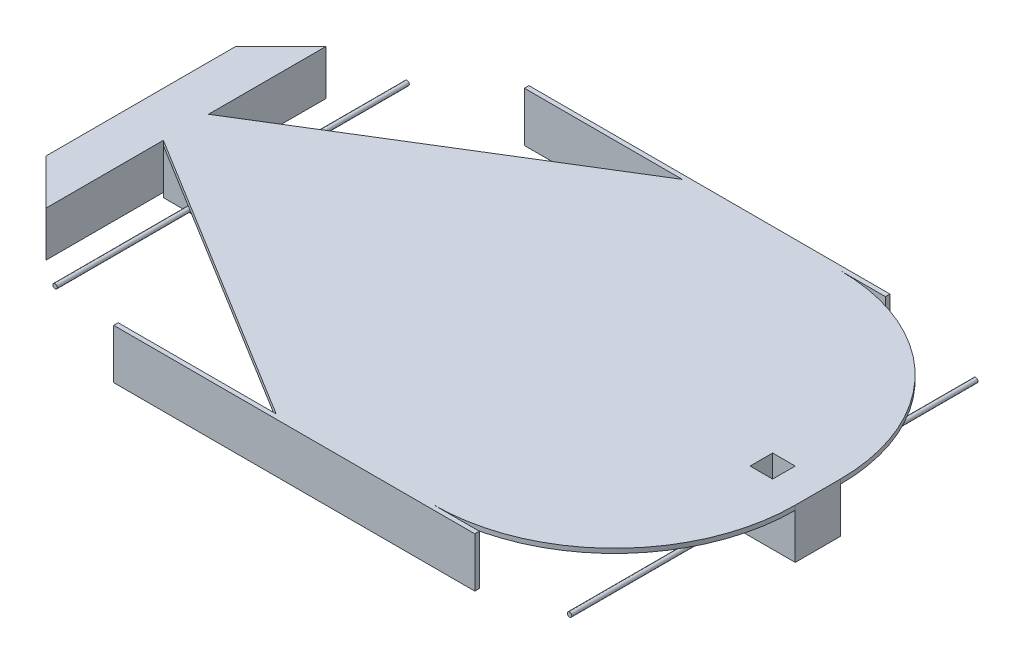
SolidWorks part; units mm, degrees
ref_plane "Front Plane" through (0, 0, 0) normal (0, 0, 1) x (1, 0, 0)
ref_plane "Top Plane" through (0, 0, 0) normal (0, 1, 0) x (1, 0, 0)
ref_plane "Right Plane" through (0, 0, 0) normal (1, 0, 0) x (0, 0, -1)
sketch "Sketch1" plane through (0, 0, 0) normal (0, 0, 1) x (1, 0, 0)
  line L1 (889, -63.5) -> (-889, -63.5)
  line L2 (889, -63.5) -> (889, 63.5)
  line L3 (889, 63.5) -> (-889, 63.5)
  line L4 (-889, -63.5) -> (-889, 63.5)
  line L5 (889, -63.5) -> (-889, 63.5) construction
  line L6 (889, 63.5) -> (-889, -63.5) construction
  point P0 (0, 0)
  point P6 (-508, -63.5)
  dimension "D1" = 1778
  dimension "D2" = 127
extrude "Boss-Extrude1" add sketch "Sketch1" along normal blind 127
sketch "Sketch2" plane through (0, 0, 127) normal (0, 0, 1) x (1, 0, 0)
  line L0 (-889, -63.5) -> (889, -63.5) construction
  line L1 (-63.5, 63.5) -> (63.5, 63.5)
  line L2 (-63.5, 63.5) -> (-63.5, -63.5)
  line L3 (-63.5, -63.5) -> (63.5, -63.5)
  line L4 (63.5, 63.5) -> (63.5, -63.5)
  line L5 (-63.5, 63.5) -> (63.5, -63.5) construction
  line L6 (-63.5, -63.5) -> (63.5, 63.5) construction
  point P0 (0, 0)
  dimension "D1" = 127
extrude "Boss-Extrude2" add sketch "Sketch2" along normal blind 508
sketch "Sketch3" plane through (0, 0, 0) normal (0, 0, -1) x (-1, 0, 0)
  line L1 (-63.5, 63.5) -> (63.5, 63.5)
  line L2 (-63.5, 63.5) -> (-63.5, -63.5)
  line L3 (-63.5, -63.5) -> (63.5, -63.5)
  line L4 (63.5, 63.5) -> (63.5, -63.5)
  line L5 (-63.5, 63.5) -> (63.5, -63.5) construction
  line L6 (-63.5, -63.5) -> (63.5, 63.5) construction
  point P0 (0, 0)
extrude "Boss-Extrude3" add sketch "Sketch3" along normal blind 508
sketch "Sketch4" plane through (0, 0, 127) normal (0, 0, 1) x (1, 0, 0)
  line L0 (-889, 0) -> (-762, 0) construction
  line L1 (-889, 63.5) -> (-889, -63.5) construction
  circle A0 centre (-762, 0) radius 6.35
  dimension "D2" = 12.7
  dimension "D1" = 127
extrude "Boss-Extrude4" add sketch "Sketch4" along normal blind 431.8 and the other way blind 558.8
sketch "Sketch6" plane through (0, 0, 127) normal (0, 0, 1) x (1, 0, 0)
  line L0 (889, 0) -> (762, 0) construction
  line L1 (889, -63.5) -> (889, 63.5) construction
  circle A0 centre (762, 0) radius 6.35
  dimension "D2" = 12.7
  dimension "D1" = 127
extrude "Boss-Extrude5" add sketch "Sketch6" along normal blind 508 and the other way blind 635
sketch "Sketch9" plane through (0, 63.5, 0) normal (0, 1, 0) x (1, 0, 0)
  line L0 (-63.5, -63.5) -> (889, -63.5) construction
  line L2 (889, -127) -> (889, 0) construction
  line L3 (0, 508) -> (0, -635) construction
  line L4 (-63.5, 508) -> (63.5, 508) construction
  line L5 (63.5, -635) -> (-63.5, -635) construction
  line L6 (-63.5, 508) -> (-63.5, -635)
  line L7 (-63.5, -635) -> (381, -635)
  line L9 (-63.5, 508) -> (381, 508)
  line L10 (889, -127) -> (889, 0)
  line L11 (-63.5, -635) -> (889, 508) construction
  line L12 (-63.5, 508) -> (889, -635) construction
  arc A0 (381, 508) -> (889, 0) centre (381, 0) cw
  arc A1 (889, -127) -> (381, -635) centre (381, -127) cw
  point P12 (412.75, -63.5)
  dimension "D2" = 508
  dimension "D1" = 952.5
extrude "Boss-Extrude7" add sketch "Sketch9" along normal blind 12.7
sketch "Sketch10" plane through (0, 63.5, 0) normal (0, 1, 0) x (1, 0, 0)
  line L0 (-63.5, -635) -> (-889, -127)
  line L1 (-889, -127) -> (-889, 0)
  line L2 (-889, 0) -> (-63.5, 508)
  line L7 (381, 508) -> (-63.5, 508)
  line L8 (-63.5, 508) -> (-63.5, -635)
  line L9 (-63.5, -635) -> (381, -635)
  line L10 (889, -127) -> (889, 0)
  line L11 (381, 508) -> (-63.5, 508)
  line L13 (-63.5, -635) -> (381, -635)
  line L14 (889, -127) -> (889, 0)
  arc A2 (889, 0) -> (381, 508) centre (381, 0) ccw
  arc A3 (381, -635) -> (889, -127) centre (381, -127) ccw
  arc A4 (889, 0) -> (381, 508) centre (381, 0) ccw
  arc A5 (381, -635) -> (889, -127) centre (381, -127) ccw
  dimension "D1" = 0
extrude "Boss-Extrude8" add sketch "Sketch10" along normal blind 12.7
sketch "Sketch11" plane through (0, 0, -508) normal (0, 0, -1) x (-1, 0, 0)
  line L0 (-63.5, 76.2) -> (-63.5, -63.5) construction
  line L1 (-381, 76.2) -> (63.5, 76.2) construction
  line L2 (-63.5, -63.5) -> (63.5, -63.5) construction
  line L3 (63.5, -63.5) -> (63.5, 76.2) construction
  line L4 (63.5, 76.2) -> (-63.5, 76.2) construction
  line L5 (0, 76.2) -> (0, -63.5) construction
  line L6 (-63.5, 6.35) -> (63.5, 6.35) construction
  line L8 (-508, -63.5) -> (508, -63.5)
  line L9 (-508, -63.5) -> (-508, 76.2)
  line L10 (-508, 76.2) -> (508, 76.2)
  line L11 (508, -63.5) -> (508, 76.2)
  line L12 (-508, -63.5) -> (508, 76.2) construction
  line L13 (-508, 76.2) -> (508, -63.5) construction
  point P13 (0, 6.35)
  dimension "D1" = 139.7
  dimension "D2" = 1016
extrude "Boss-Extrude9" add sketch "Sketch11" along normal blind 12.7
sketch "Sketch12" plane through (0, 0, 635) normal (0, 0, 1) x (1, 0, 0)
  line L0 (-63.5, -63.5) -> (-63.5, 76.2) construction
  line L1 (-63.5, 76.2) -> (63.5, 76.2) construction
  line L2 (-63.5, 76.2) -> (381, 76.2) construction
  line L3 (63.5, 76.2) -> (63.5, -63.5) construction
  line L4 (63.5, -63.5) -> (-63.5, -63.5) construction
  line L5 (0, 76.2) -> (0, -63.5) construction
  line L6 (-63.5, 6.35) -> (63.5, 6.35) construction
  line L7 (63.5, -63.5) -> (889, -63.5) construction
  line L8 (-508, 76.2) -> (508, 76.2)
  line L9 (-508, 76.2) -> (-508, -63.5)
  line L10 (-508, -63.5) -> (508, -63.5)
  line L11 (508, 76.2) -> (508, -63.5)
  line L12 (-508, 76.2) -> (508, -63.5) construction
  line L13 (-508, -63.5) -> (508, 76.2) construction
  point P13 (0, 6.35)
  dimension "D1" = 1016
extrude "Boss-Extrude10" add sketch "Sketch12" along normal blind 12.7
sketch "Sketch13" plane through (0, 76.2, 0) normal (0, 1, 0) x (1, 0, 0)
  line L1 (-1016, 0) -> (-1016, 203.2)
  line L2 (-889, 0) -> (-1016, 0)
  line L3 (-889, 0) -> (-889, -127)
  line L4 (-889, -127) -> (-1016, -127)
  line L5 (-1016, 0) -> (-1016, -127)
  line L6 (-1016, 203.2) -> (-889, 330.2)
  line L7 (-889, 330.2) -> (-889, 0)
  line L8 (-1016, -127) -> (-1016, -330.2)
  line L9 (-1016, -330.2) -> (-889, -457.2)
  line L10 (-889, -457.2) -> (-889, -127)
  line L11 (-889, 330.2) -> (-889, -457.2)
  line L12 (-1016, -330.2) -> (-1016, 203.2)
  line M17 (-889, 0) -> (-889, -127)
  dimension "D1" = 127
  dimension "D2" = 127
  dimension "D3" = 203.2
  dimension "D4" = 203.2
  dimension "D5" = 330.2
  dimension "D6" = 330.2
extrude "Boss-Extrude11" add sketch "Sketch13" against normal blind 127 contours L7 L6 L1 L2 | L9 L10 L4 L8 | L2 L5 L4 M17
sketch "Sketch15" plane through (0, 76.2, 0) normal (0, 1, 0) x (1, 0, 0)
  line L0 (889, -63.5) -> (762, -63.5) construction
  line L1 (889, -127) -> (889, 0) construction
  line L3 (793.75, -31.75) -> (730.25, -31.75)
  line L4 (793.75, -31.75) -> (793.75, -95.25)
  line L5 (793.75, -95.25) -> (730.25, -95.25)
  line L6 (730.25, -31.75) -> (730.25, -95.25)
  line L7 (793.75, -31.75) -> (730.25, -95.25) construction
  line L8 (793.75, -95.25) -> (730.25, -31.75) construction
  dimension "D1" = 127
  dimension "D2" = 63.5
  dimension "D3" = 63.5
extrude "Cut-Extrude1" cut sketch "Sketch15" against normal blind 63.5
